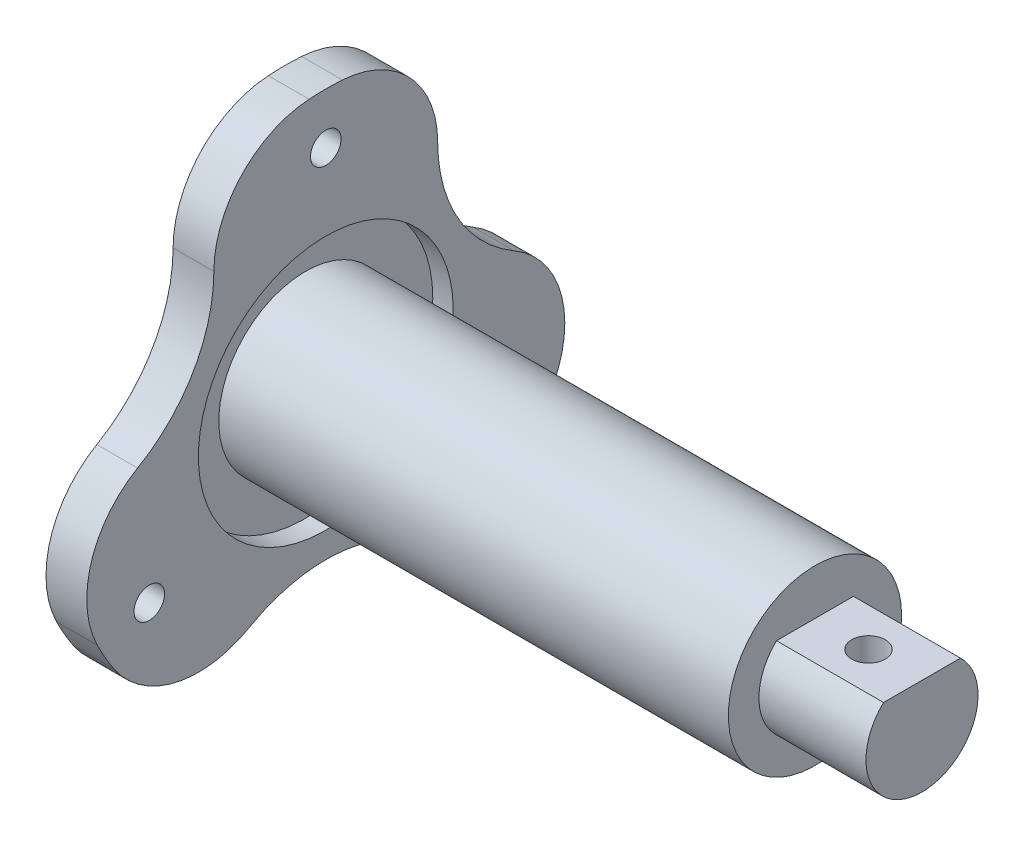
SolidWorks part; units mm, degrees
material "6061 合金"
ref_plane "前视基准面" through (0, 0, 0) normal (0, 0, 1) x (1, 0, 0)
ref_plane "上视基准面" through (0, 0, 0) normal (0, 1, 0) x (1, 0, 0)
ref_plane "右视基准面" through (0, 0, 0) normal (1, 0, 0) x (0, 0, -1)
sketch "草图1" plane through (0, 0, 0) normal (1, 0, 0) x (0, 0, -1)
  circle A0 centre (0, 0) radius 25
  dimension "D1" = 50
extrude "凸台-拉伸1" add sketch "草图1" along normal blind 3
sketch "草图2" plane through (3, 0, 0) normal (1, 0, 0) x (0, 0, -1)
  line L0 (25.9808, 15) -> (0, 0)
  line L1 (0, 0) -> (0, 27.7673)
  circle A0 centre (25.9808, 15) radius 15
  circle M1 centre (0, 0) radius 25
  dimension "D1" = 60
  dimension "D3" = 30
  dimension "D2" = 30
extrude "切除-拉伸1" cut sketch "草图2" against normal blind 3 contours A0 L0 M1 | L0 A0 M1
pattern_circular "阵列(圆周)1" count 3 over 360 about axis through (0, 0, 0) along (1, 0, 0) of "切除-拉伸1"
fillet "圆角1" radius 10 6 edges at (1.5, 0.0321, -25) (1.5, 21.6346, -12.5278) (1.5, -21.6667, 12.4722) (1.5, -21.6667, -12.4722) (1.5, 21.6346, 12.5278) (1.5, 0.0321, 25)
sketch "草图3" plane through (3, 0, 0) normal (1, 0, 0) x (0, 0, -1)
  circle A0 centre (0, 0) radius 8.5
  dimension "D1" = 17
extrude "凸台-拉伸2" add sketch "草图3" along normal blind 48
sketch "草图5" plane through (0, 0, 0) normal (-1, 0, 0) x (0, 0, 1)
  circle A0 centre (0, 20) radius 1.5
  dimension "D1" = 3
  dimension "D2" = 0
  dimension "D3" = 20
extrude "切除-拉伸2" cut sketch "草图5" against normal blind 52
pattern_circular "阵列(圆周)2" count 3 over 360 about axis through (0, 0, 0) along (1, 0, 0) of "切除-拉伸2"
sketch "草图7" plane through (51, 0, 0) normal (1, 0, 0) x (0, 0, -1)
  circle A0 centre (0, 0) radius 5.5
  dimension "D1" = 11
extrude "凸台-拉伸3" add sketch "草图7" along normal blind 10.5
sketch "草图8" plane through (61.5, 0, 0) normal (1, 0, 0) x (0, 0, -1)
  line L0 (-5.1472, 4) -> (5.1472, 4)
  line L1 (-5.1472, 4) -> (-5.1472, 7.679)
  line L2 (-5.1472, 7.679) -> (5.1472, 7.679)
  line L3 (5.1472, 7.679) -> (5.1472, 4)
  line L4 (0, -1000) -> (0, 49000) construction
  point P6 (0, 4)
  dimension "D1" = 4
  dimension "D2" = 3.679
  dimension "D3" = 10.2944
extrude "切除-拉伸3" cut sketch "草图8" against normal up to surface (10.5 mm away) up to face at (51, 0, -5.5)
ref_plane "基准面1" through (47.7, 0, 0) normal (1, 0, 0) x (0, 0, -1)
sketch "草图11" plane through (47.7, 0, 0) normal (1, 0, 0) x (0, 0, -1)
  circle A0 centre (0, 0) radius 8.1
  circle A1 centre (0, 0) radius 8.5
  dimension "D1" = 16.2
  dimension "D2" = 17
sketch "草图12" plane through (3, 0, 0) normal (1, 0, 0) x (0, 0, -1)
  circle A0 centre (0, 0) radius 8.5 construction
  circle A1 centre (0, 0) radius 8.5
  circle A2 centre (0, 0) radius 12.5
  dimension "D1" = 25
extrude "切除-拉伸6" cut sketch "草图12" against normal blind 2
sketch "草图13" plane through (0, 0, 0) normal (-1, 0, 0) x (0, 0, 1)
  circle A0 centre (0, 20) radius 1.5 construction
  circle A1 centre (-17.3205, -10) radius 1.5 construction
  circle A2 centre (17.3205, -10) radius 1.5 construction
  circle A3 centre (0, 20) radius 1.5
  circle A4 centre (-17.3205, -10) radius 1.5
  circle A5 centre (17.3205, -10) radius 1.5
  arc A12 (-18.4641, 2.0193) -> (-10.9808, 14.9807) centre (-25.9808, 15) ccw
  arc A13 (-18.4641, 2.0193) -> (-22.4216, -11.0576) centre (-13.453, -6.6346) ccw
  arc A14 (-22.4216, -11.0576) -> (-20.787, -13.8889) centre (0, 0) ccw
  arc A15 (-20.787, -13.8889) -> (-7.4833, -17) centre (-12.4722, -8.3333) ccw
  arc A16 (7.4833, -17) -> (-7.4833, -17) centre (0, -30) ccw
  arc A17 (7.4833, -17) -> (20.787, -13.8889) centre (12.4722, -8.3333) ccw
  arc A18 (20.787, -13.8889) -> (22.4216, -11.0576) centre (0, 0) ccw
  arc A19 (22.4216, -11.0576) -> (18.4641, 2.0193) centre (13.453, -6.6346) ccw
  arc A20 (10.9808, 14.9807) -> (18.4641, 2.0193) centre (25.9808, 15) ccw
  arc A21 (10.9808, 14.9807) -> (1.6346, 24.9465) centre (0.9808, 14.9679) ccw
  arc A22 (1.6346, 24.9465) -> (-1.6346, 24.9465) centre (0, 0) ccw
  arc A23 (-1.6346, 24.9465) -> (-10.9808, 14.9807) centre (-0.9808, 14.9679) ccw
  arc A24 (-18.4641, 2.0193) -> (-10.9808, 14.9807) centre (-25.9808, 15) ccw
  arc A25 (-18.4641, 2.0193) -> (-22.4216, -11.0576) centre (-13.453, -6.6346) ccw
  arc A26 (-22.4216, -11.0576) -> (-20.787, -13.8889) centre (0, 0) ccw
  arc A27 (-20.787, -13.8889) -> (-7.4833, -17) centre (-12.4722, -8.3333) ccw
  arc A28 (7.4833, -17) -> (-7.4833, -17) centre (0, -30) ccw
  arc A29 (7.4833, -17) -> (20.787, -13.8889) centre (12.4722, -8.3333) ccw
  arc A30 (20.787, -13.8889) -> (22.4216, -11.0576) centre (0, 0) ccw
  arc A31 (22.4216, -11.0576) -> (18.4641, 2.0193) centre (13.453, -6.6346) ccw
  arc A32 (10.9808, 14.9807) -> (18.4641, 2.0193) centre (25.9808, 15) ccw
  arc A33 (10.9808, 14.9807) -> (1.6346, 24.9465) centre (0.9808, 14.9679) ccw
  arc A34 (1.6346, 24.9465) -> (-1.6346, 24.9465) centre (0, 0) ccw
  arc A35 (-1.6346, 24.9465) -> (-10.9808, 14.9807) centre (-0.9808, 14.9679) ccw
  dimension "D1" = 0
extrude "凸台-拉伸4" add sketch "草图13" along normal blind 1
sketch "草图14" plane through (0, 4, 0) normal (0, 1, 0) x (1, 0, 0)
  line L0 (51, 3.7749) -> (61.5, 3.7749) construction
  line L1 (61.5, -3.7749) -> (61.5, 3.7749) construction
  circle A0 centre (56.25, 0) radius 1.5
  point P5 (56.25, 3.7749)
  point P8 (61.5, 0)
  dimension "D1" = 3
hole_wizard "M4 螺纹孔1" positions "草图15" profile "草图16" tap size "M4" standard "GB" end condition through all
sketch "草图15" plane through (0, 4, 0) normal (0, 1, 0) x (1, 0, 0)
  point P0 (56.25, 0)
sketch "草图16" plane through (56.25, 4, 0) normal (1, 0, 0) x (0, 0, 1)
  line L0 (0, 0) -> (0, 22.3333)
  line L1 (0, 22.3333) -> (1.65, 22.3333)
  line L2 (1.65, 22.3333) -> (1.65, 0)
  line L5 (1.65, 0) -> (0, 0)
  line L11 (0, -6.35) -> (0, 107.95) construction
  dimension "通孔螺纹孔钻头直径" = 3.3
  dimension "通孔螺纹孔钻头深度" = 22.3333
cosmetic thread "孔螺蚊线1" parameters "D2"=4
